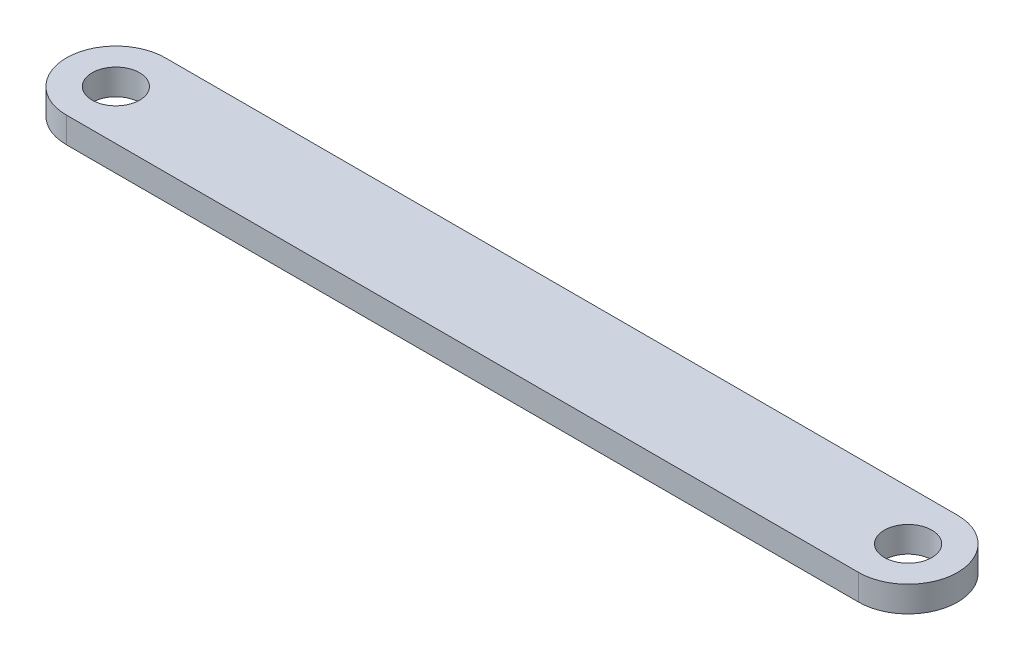
SolidWorks part; units mm, degrees
ref_plane "Front Plane" through (0, 0, 0) normal (0, 0, 1) x (1, 0, 0)
ref_plane "Top Plane" through (0, 0, 0) normal (0, 1, 0) x (1, 0, 0)
ref_plane "Right Plane" through (0, 0, 0) normal (1, 0, 0) x (0, 0, -1)
sketch "Sketch1" plane through (0, 0, 0) normal (0, 1, 0) x (1, 0, 0)
  line L0 (-100, 0) -> (100, 0) construction
  line L1 (-100, 12.5) -> (100, 12.5)
  line L2 (-100, -12.5) -> (100, -12.5)
  arc A0 (-100, 12.5) -> (-100, -12.5) centre (-100, 0) ccw
  arc A1 (100, -12.5) -> (100, 12.5) centre (100, 0) ccw
  circle A2 centre (100, 0) radius 6
  circle A3 centre (-100, 0) radius 6
  point P2 (0, 0)
  dimension "D2" = 12.5
  dimension "D3" = 12
  dimension "D1" = 200
extrude "Boss-Extrude1" add sketch "Sketch1" along normal mid plane 6.5
